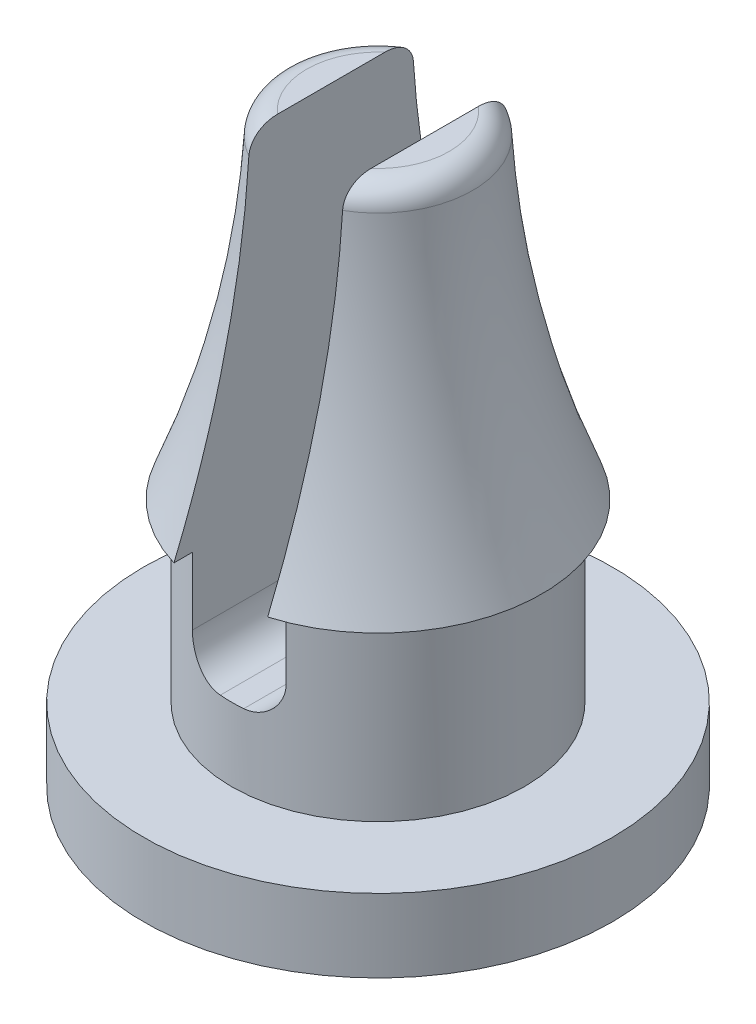
SolidWorks part; units mm, degrees
ref_plane "Front Plane" through (0, 0, 0) normal (0, 0, 1) x (1, 0, 0)
ref_plane "Top Plane" through (0, 0, 0) normal (0, 1, 0) x (1, 0, 0)
ref_plane "Right Plane" through (0, 0, 0) normal (1, 0, 0) x (0, 0, -1)
sketch "Sketch1" plane through (0, 0, 0) normal (0, 0, 1) x (1, 0, 0)
  line L0 (0, 0) -> (-5.08, 0)
  line L1 (-5.08, 0) -> (-5.08, 1.5875)
  line L2 (-5.08, 1.5875) -> (-3.175, 1.5875)
  line L3 (-3.175, 1.5875) -> (-3.175, 5.3975)
  line L6 (-1.5455, 12.7) -> (0, 12.7)
  line L7 (0, 12.7) -> (0, 0)
  line L8 (-3.556, 5.3975) -> (-3.175, 5.3975)
  arc A0 (-3.556, 5.3975) -> (-2.0528, 12.2196) centre (-23.6109, 13.3931) ccw
  arc A1 (-2.0528, 12.2196) -> (-1.5455, 12.7) centre (-1.5455, 12.192) cw
  point P12 (-2.032, 12.7)
  dimension "D8" = 1.5455
  dimension "D9" = 0.508
  dimension "D1" = 5.08
  dimension "D2" = 1.5875
  dimension "D3" = 3.81
  dimension "D4" = 3.556
  dimension "D5" = 3.175
  dimension "D6" = 12.7
  dimension "D7" = 2.032
revolve "Revolve1" add sketch "Sketch1" angle 360 about L7
sketch "Sketch2" plane through (0, 0, 0) normal (0, 0, 1) x (1, 0, 0)
  line L0 (1.5455, 12.7) -> (-1.5455, 12.7) construction
  line L1 (-0.254, 3.175) -> (0.254, 3.175)
  line L2 (-1.016, 3.937) -> (-1.016, 12.7)
  line L3 (-1.016, 12.7) -> (1.016, 12.7)
  line L4 (1.016, 3.937) -> (1.016, 12.7)
  line L5 (-1.016, 3.175) -> (1.016, 12.7) construction
  line L6 (-1.016, 12.7) -> (1.016, 3.175) construction
  arc A0 (0.254, 3.175) -> (1.016, 3.937) centre (0.254, 3.937) ccw
  arc A1 (-0.254, 3.175) -> (-1.016, 3.937) centre (-0.254, 3.937) cw
  point P0 (0, 7.9375)
  point P11 (0, 12.7)
  dimension "D3" = 0.762
  dimension "D1" = 2.032
  dimension "D2" = 9.525
extrude "Cut-Extrude1" cut sketch "Sketch2" against normal through all and the other way through all
